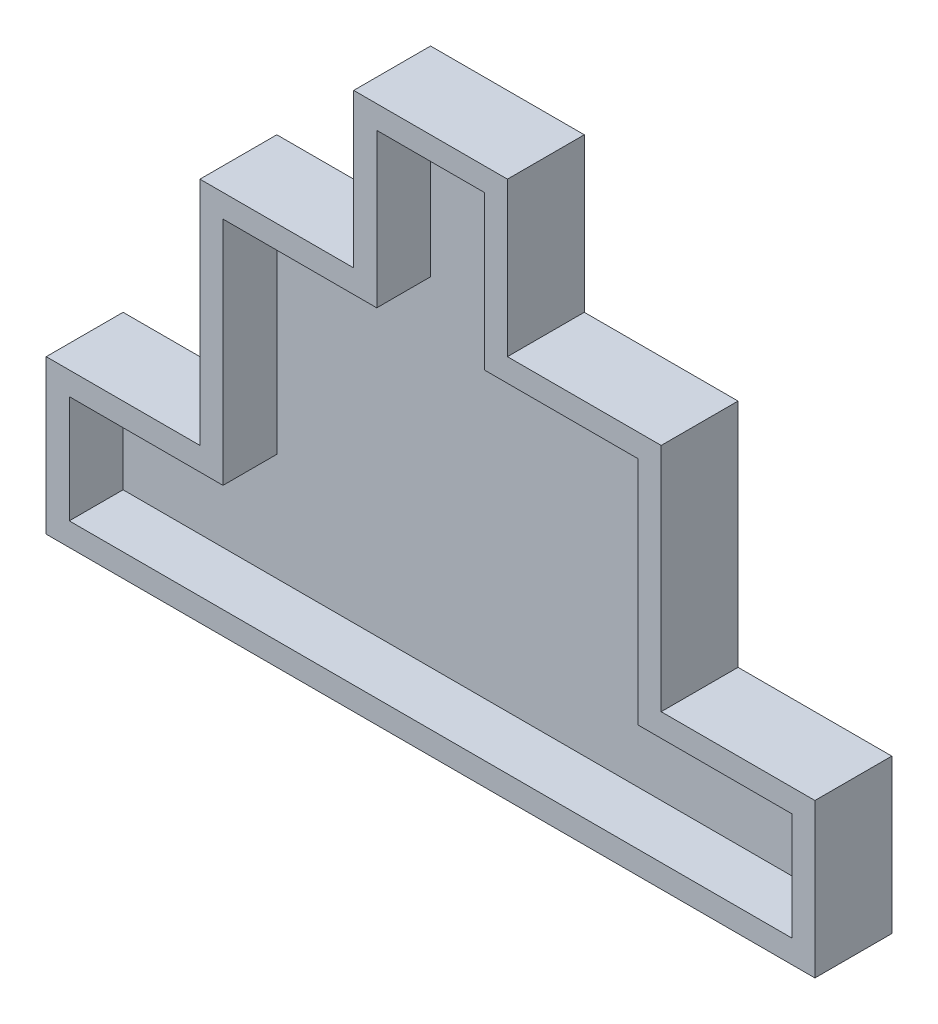
SolidWorks part; units mm, degrees
ref_plane "Front Plane" through (0, 0, 0) normal (0, 0, 1) x (1, 0, 0)
ref_plane "Top Plane" through (0, 0, 0) normal (0, 1, 0) x (1, 0, 0)
ref_plane "Right Plane" through (0, 0, 0) normal (1, 0, 0) x (0, 0, -1)
sketch "Sketch1" plane through (0, 0, 0) normal (0, 0, 1) x (1, 0, 0)
  line L0 (75, 0) -> (-75, 0)
  line L1 (-75, 0) -> (-75, 30)
  line L2 (-75, 30) -> (-45, 30)
  line L3 (-45, 30) -> (-45, 75)
  line L4 (-45, 75) -> (-15, 75)
  line L5 (-15, 75) -> (-15, 105)
  line L6 (-15, 105) -> (15, 105)
  line L7 (0, -20.0529) -> (0, 136.1306) construction
  line L8 (15, 75) -> (15, 105)
  line L9 (45, 30) -> (45, 75)
  line L10 (75, 30) -> (45, 30)
  line L11 (75, 0) -> (75, 30)
  line L12 (15, 75) -> (45, 75)
  point P12 (0, 105)
  point P17 (0, 0)
  dimension "D1" = 75
  dimension "D2" = 30
  dimension "D3" = 30
  dimension "D4" = 45
  dimension "D5" = 30
  dimension "D6" = 30
extrude "Boss-Extrude1" add sketch "Sketch1" along normal blind 4.5
sketch "Sketch2" plane through (0, 0, 4.5) normal (0, 0, 1) x (1, 0, 0)
  line L0 (1.1688, 4.5) -> (-70.5, 4.5)
  line L1 (-70.5, 4.5) -> (-70.5, 25.5)
  line L2 (-70.5, 25.5) -> (-40.5, 25.5)
  line L3 (-40.5, 25.5) -> (-40.5, 70.5)
  line L4 (-40.5, 70.5) -> (-10.5, 70.5)
  line L5 (-10.5, 70.5) -> (-10.5, 100.5)
  line L6 (-10.5, 100.5) -> (10.5, 100.5)
  line L7 (10.5, 100.5) -> (10.5, 70.5)
  line L8 (10.5, 70.5) -> (40.5, 70.5)
  line L9 (40.5, 70.5) -> (40.5, 25.5)
  line L10 (40.5, 25.5) -> (70.5, 25.5)
  line L11 (70.5, 25.5) -> (70.5, 4.5)
  line L12 (70.5, 4.5) -> (1.1688, 4.5)
  line L13 (15, 105) -> (-15, 105) construction
  line L14 (-15, 75) -> (-45, 75) construction
  line L15 (45, 75) -> (15, 75) construction
  line L16 (-45, 75) -> (-45, 30) construction
  line L17 (45, 30) -> (45, 75) construction
  line L18 (15, 75) -> (15, 105) construction
  line L19 (-15, 105) -> (-15, 75) construction
  line L20 (-75, 30) -> (-75, 0) construction
  line L21 (-45, 30) -> (-75, 30) construction
  line L22 (-75, 0) -> (75, 0) construction
  line L23 (75, 30) -> (45, 30) construction
  line L24 (75, 0) -> (75, 30) construction
  line L25 (-75, 0) -> (-75, 30)
  line L26 (-75, 30) -> (-45, 30)
  line L27 (-45, 30) -> (-45, 75)
  line L28 (-45, 75) -> (-15, 75)
  line L29 (-15, 75) -> (-15, 105)
  line L30 (-15, 105) -> (15, 105)
  line L31 (15, 105) -> (15, 75)
  line L32 (15, 75) -> (45, 75)
  line L33 (45, 75) -> (45, 30)
  line L34 (45, 30) -> (75, 30)
  line L35 (75, 30) -> (75, 0)
  line L36 (75, 0) -> (-75, 0)
  point P17 (-30, 75)
  dimension "D1" = 4.5
  dimension "D2" = 4.5
  dimension "D3" = 4.5
  dimension "D4" = 4.5
  dimension "D5" = 4.5
  dimension "D6" = 4.5
  dimension "D7" = 4.5
  dimension "D8" = 4.5
  dimension "D9" = 4.5
  dimension "D10" = 4.5
  dimension "D11" = 4.5
  dimension "D12" = 4.5
extrude "Boss-Extrude2" add sketch "Sketch2" along normal blind 10.5
